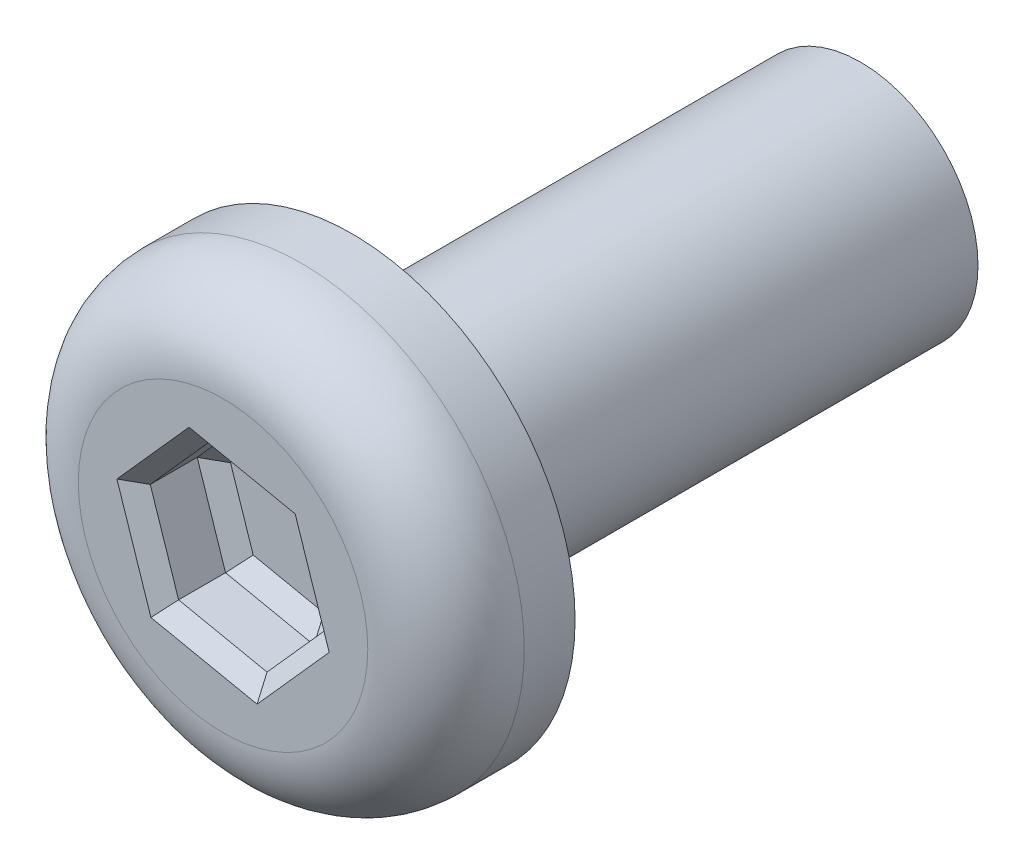
SolidWorks part; units mm, degrees
ref_plane "前视基准面" through (0, 0, 0) normal (0, 0, 1) x (1, 0, 0)
ref_plane "上视基准面" through (0, 0, 0) normal (0, 1, 0) x (1, 0, 0)
ref_plane "右视基准面" through (0, 0, 0) normal (1, 0, 0) x (0, 0, -1)
sketch "草图1" plane through (0, 0, 0) normal (0, 0, 1) x (1, 0, 0)
  circle A0 centre (0, 0) radius 2.85
  dimension "D1" = 5.7
extrude "凸台-拉伸1" add sketch "草图1" along normal blind 1.65
sketch "草图2" plane through (0, 0, 0) normal (0, 0, -1) x (-1, 0, 0)
  circle A0 centre (0, 0) radius 1.5
  dimension "D1" = 3
extrude "凸台-拉伸2" add sketch "草图2" along normal blind 6.5
fillet "圆角1" radius 1 1 edges at (2.85, 0, 1.65)
sketch "草图3" plane through (0, 0, 1.65) normal (0, 0, 1) x (1, 0, 0)
  line L1 (0.3622, -1.0964) -> (1.1306, -0.2345)
  line L2 (1.1306, -0.2345) -> (0.7684, 0.8619)
  line L3 (0.7684, 0.8619) -> (-0.3622, 1.0964)
  line L4 (-0.3622, 1.0964) -> (-1.1306, 0.2345)
  line L5 (-1.1306, 0.2345) -> (-0.7684, -0.8619)
  line L6 (-0.7684, -0.8619) -> (0.3622, -1.0964)
  circle A0 centre (0, 0) radius 1 construction
  dimension "D1" = 2
extrude "切除-拉伸1" cut sketch "草图3" against normal blind 1
chamfer "倒角1" distance 0.2 angle 45 12 edges at (0.7464, -0.6655, 1.65) (0.9495, 0.3137, 1.65) (0.2031, 0.9792, 1.65) (-0.7464, 0.6655, 1.65) (-0.9495, -0.3137, 1.65) (-0.2031, -0.9792, 1.65) (-0.9495, -0.3137, 0.65) (-0.7464, 0.6655, 0.65) (0.2031, 0.9792, 0.65) (0.9495, 0.3137, 0.65) (0.7464, -0.6655, 0.65) (-0.2031, -0.9792, 0.65)
